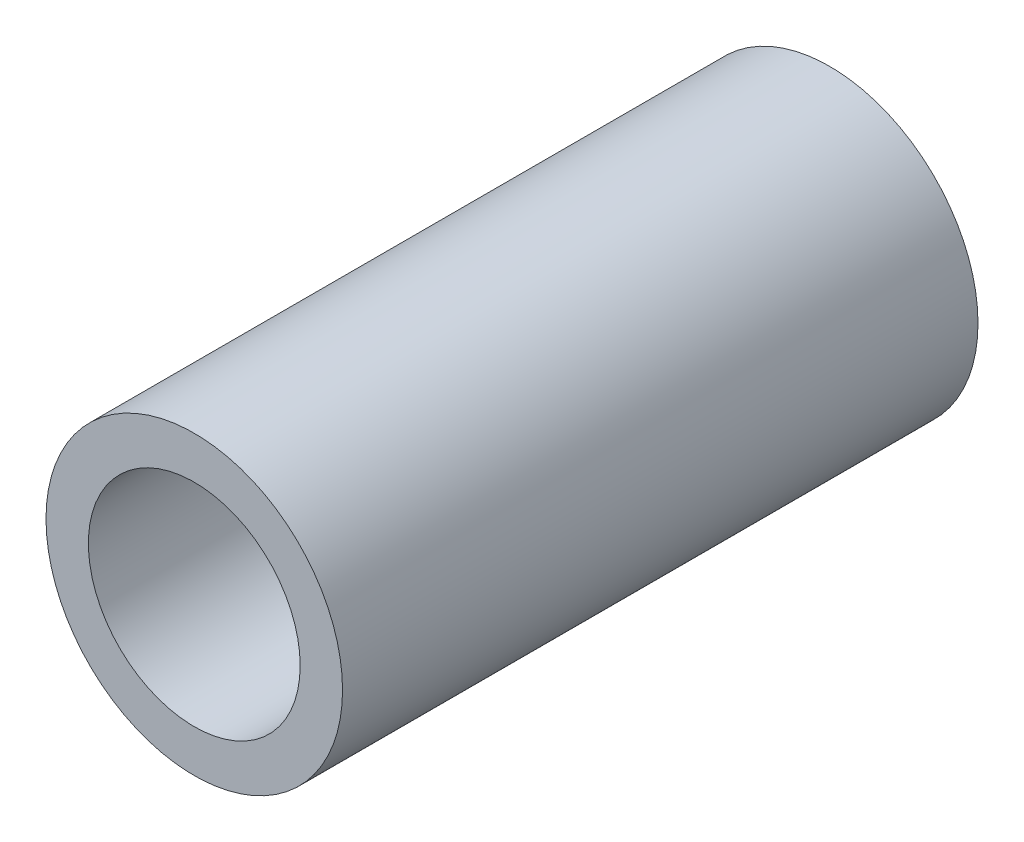
SolidWorks part; units mm, degrees
ref_plane "Спереди" through (0, 0, 0) normal (0, 0, 1) x (1, 0, 0)
ref_plane "Сверху" through (0, 0, 0) normal (0, 1, 0) x (1, 0, 0)
ref_plane "Справа" through (0, 0, 0) normal (1, 0, 0) x (0, 0, -1)
sketch "Эскиз1" plane through (0, 0, 0) normal (0, 0, 1) x (1, 0, 0)
  circle A0 centre (0, 0) radius 5
  dimension "D1" = 10
extrude "Вытянуть-Тонкостенный1" add sketch "Эскиз1" along normal blind 30 thin contours A0
